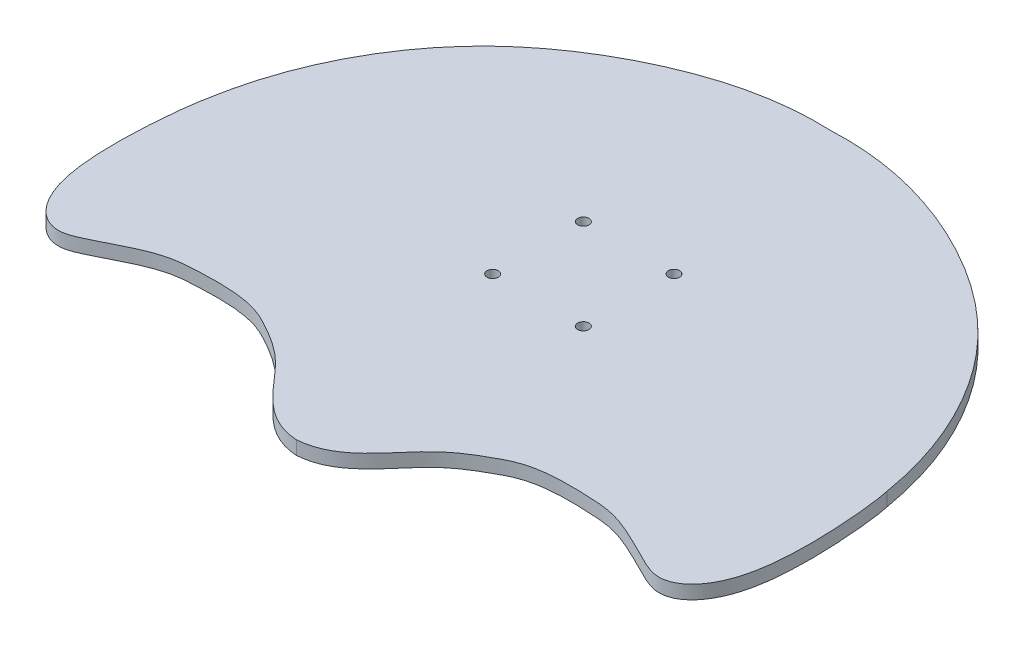
SolidWorks part; units mm, degrees
ref_plane "Front Plane" through (0, 0, 0) normal (0, 0, 1) x (1, 0, 0)
ref_plane "Top Plane" through (0, 0, 0) normal (0, 1, 0) x (1, 0, 0)
ref_plane "Right Plane" through (0, 0, 0) normal (1, 0, 0) x (0, 0, -1)
sketch "Sketch3" plane through (0, 0, 0) normal (0, 1, 0) x (1, 0, 0)
  line L0 (0, 0) -> (0, 159.1899) construction
  line L1 (0, 0) -> (0, -140.5301) construction
  line L2 (0, 0) -> (-190.5, 0) construction
  line L3 (0, 0) -> (190.5, 0) construction
  spline S0 degree 3 poles (-190.5, 0) (-184.3927, 37.537) (-157.2613, 93.9641) (-82.3875, 146.6227) (-31.3114, 160.7999) (0, 159.1899) knots 0 0 0 0 0.424401 0.65637 1 1 1 1
  spline S1 degree 3 poles (-190.5, 0) (-192.064, -4.9635) (-201.9672, -83.3146) (-174.6966, -109.29) (-151.6301, -100.568) (-131.4108, -87.7198) (-96.8436, -85.3754) (-78.6925, -86.2588) (-58.8335, -96.8794) (-37.3059, -109.9358) (-21.3496, -139.1148) (0, -140.5301) knots 0 0 0 0 0.166997 0.292321 0.319633 0.426735 0.458914 0.609242 0.64191 0.766802 1 1 1 1
  spline S2 degree 3 poles (190.5, 0) (192.064, -4.9635) (201.9672, -83.3146) (174.6966, -109.29) (151.6301, -100.568) (131.4108, -87.7198) (96.8436, -85.3754) (78.6925, -86.2588) (58.8335, -96.8794) (37.3059, -109.9358) (21.3496, -139.1148) (0, -140.5301) knots 0 0 0 0 0.166997 0.292321 0.319633 0.426735 0.458914 0.609242 0.64191 0.766802 1 1 1 1
  spline S3 degree 3 poles (190.5, 0) (184.3927, 37.537) (157.2613, 93.9641) (82.3875, 146.6227) (31.3114, 160.7999) (0, 159.1899) knots 0 0 0 0 0.424401 0.65637 1 1 1 1
  dimension "D1" = 381
  dimension "D2" = 299.72
  dimension "D3" = 159.1899
  dimension "D4" = 86.8953
  dimension "D5" = 104.4979
  dimension "D6" = 29.1616
  dimension "D7" = 92.2742
  dimension "D8" = 108.411
  dimension "D9" = 67.4883
  dimension "D10" = 43.7314
  dimension "D11" = 117.6915
  dimension "D12" = 162.2568
  dimension "D13" = 89.4522
  dimension "D14" = 140.1036
  dimension "D15" = 175.0666
  dimension "D16" = 50.2669
  dimension "D17" = 101.3666
  dimension "D18" = 138.1225
  dimension "D19" = 155.1557
  dimension "D20" = 192.0074
  dimension "D21" = 193.9268
  dimension "D23" = 76.6666
extrude "Boss-Extrude1" add sketch "Sketch3" along normal blind 7.62 from surface at 0 starting at plane "Top Plane"
sketch "Sketch5" plane through (0, 0, 0) normal (0, -1, 0) x (1, 0, 0)
  line L0 (0, 0) -> (0, -20.32) construction
  line L1 (25.4, -45.72) -> (-25.4, -45.72)
  line L2 (25.4, -45.72) -> (25.4, 5.08)
  line L3 (25.4, 5.08) -> (-25.4, 5.08)
  line L4 (-25.4, -45.72) -> (-25.4, 5.08)
  line L5 (25.4, -45.72) -> (-25.4, 5.08) construction
  line L6 (25.4, 5.08) -> (-25.4, -45.72) construction
  point P0 (0, -20.32)
  point P3 (0, -20.32)
  dimension "D1" = 20.32
  dimension "D2" = 50.8
  dimension "D3" = 50.8
hole_wizard "1/4 (0.25) Diameter Hole1" positions "Sketch6" profile "Sketch7" hole size "1/4" standard "ANSI Inch" end condition through all
sketch "Sketch6" plane through (0, 0, 0) normal (0, -1, 0) x (-1, 0, 0)
  point P0 (-25.4, 45.72)
  point P3 (25.4, 45.72)
  point P6 (25.4, -5.08)
  point P9 (-25.4, -5.08)
sketch "Sketch7" plane through (25.4, 0, -45.72) normal (1, 0, 0) x (0, 0, -1)
  line L0 (0, 0) -> (0, 7.62)
  line L1 (0, 7.62) -> (3.175, 7.62)
  line L2 (3.175, 7.62) -> (3.175, 0)
  line L5 (3.175, 0) -> (0, 0)
  line L11 (0, -6.35) -> (0, 107.95) construction
  dimension "Thru Hole Dia." = 6.35
  dimension "Thru Hole Depth" = 7.62
equation "\"Plate thickness\"= .3"
equation "\"D1@Boss-Extrude1\"=\"Plate thickness\""
equation "\"Bracket Alignment\"= .80"
equation "\"D1@Sketch5\"=\"Bracket Alignment\""
